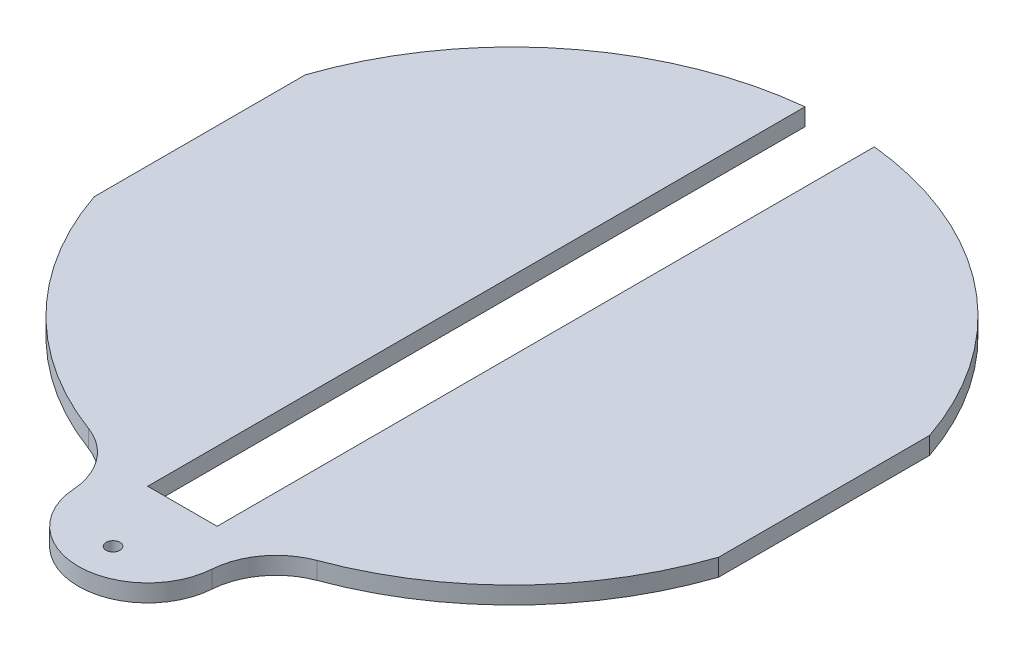
SolidWorks part; units mm, degrees
ref_plane "Front Plane" through (0, 0, 0) normal (0, 0, 1) x (1, 0, 0)
ref_plane "Top Plane" through (0, 0, 0) normal (0, 1, 0) x (1, 0, 0)
ref_plane "Right Plane" through (0, 0, 0) normal (1, 0, 0) x (0, 0, -1)
sketch "Sketch2" plane through (0, 0, 0) normal (0, 1, 0) x (1, 0, 0)
  line L0 (6.35, 63.5) -> (57.15, 63.5)
  line L1 (-57.15, -63.5) -> (-12.7, -63.5)
  line L2 (-57.15, -63.5) -> (-57.15, 63.5)
  line L3 (-57.15, 63.5) -> (-6.35, 63.5)
  line L4 (57.15, -63.5) -> (57.15, 63.5)
  line L5 (-57.15, -63.5) -> (57.15, 63.5) construction
  line L6 (-57.15, 63.5) -> (57.15, -63.5) construction
  line L7 (-6.35, -57.15) -> (6.35, -57.15)
  line L8 (-6.35, -57.15) -> (-6.35, 63.5)
  line L10 (6.35, -57.15) -> (6.35, 63.5)
  line L11 (-6.35, -57.15) -> (6.35, 63.5) construction
  line L12 (-6.35, 63.5) -> (6.35, -57.15) construction
  line L13 (12.7, -63.5) -> (57.15, -63.5)
  arc A0 (-12.7, -63.5) -> (12.7, -63.5) centre (0, -63.5) ccw
  point P0 (0, 0)
  point P6 (0, 3.175)
  point P12 (0, 0)
  point P15 (0, 0)
  dimension "D5" = 12.7
  dimension "D1" = 127
  dimension "D2" = 114.3
  dimension "D3" = 12.7
  dimension "D4" = 120.65
extrude "Boss-Extrude1" add sketch "Sketch2" along normal blind 3.175 contours L3 L8 L7 L10 L0 L4 L13 A0 L1 L2
sketch "Sketch3" plane through (0, 3.175, 0) normal (0, 1, 0) x (1, 0, 0)
  line L1 (-6.35, -57.15) -> (6.35, -57.15) construction
  circle A0 centre (0, -69.85) radius 1.27
  dimension "D1" = 2.54
  dimension "D2" = 12.7
extrude "Cut-Extrude1" cut sketch "Sketch3" against normal through all
sketch "Sketch4" plane through (0, 3.175, 0) normal (0, 1, 0) x (1, 0, 0)
  line L0 (-6.35, 3.175) -> (83.1266, 3.175) construction
  line L2 (-6.35, -57.15) -> (-6.35, 63.5) construction
  line L7 (0, 0) -> (0, 96.6328) construction
  line L8 (6.35, 63.5) -> (57.15, 63.5) construction
  line L9 (-12.7, -63.5) -> (-12.7, -55.798)
  line L10 (-57.15, 63.5) -> (57.15, 63.5)
  line L11 (-57.15, 63.5) -> (-57.15, 22.4878)
  line L12 (-57.15, -63.5) -> (-12.7, -63.5)
  line L13 (57.15, 63.5) -> (57.15, 22.4878)
  line L14 (12.7, -63.5) -> (12.7, -55.798)
  line L15 (57.15, -16.1378) -> (57.15, -63.5)
  line L16 (-57.15, -16.1378) -> (-57.15, -63.5)
  line L17 (12.7, -63.5) -> (57.15, -63.5)
  arc A1 (-57.15, -16.1378) -> (-12.7, -55.798) centre (0, 3.175) ccw
  arc A2 (57.15, 22.4878) -> (-57.15, 22.4878) centre (0, 3.175) ccw
  arc A3 (12.7, -55.798) -> (57.15, -16.1378) centre (0, 3.175) ccw
  line M11 (-57.15, 63.5) -> (-57.15, -63.5)
  line M12 (-57.15, -63.5) -> (-12.7, -63.5)
  line M14 (12.7, -63.5) -> (57.15, -63.5)
  line M15 (57.15, -63.5) -> (57.15, 63.5)
  line M16 (57.15, 63.5) -> (6.35, 63.5)
  line M17 (6.35, 63.5) -> (6.35, -57.15)
  line M19 (-6.35, -57.15) -> (-6.35, 63.5)
  line M20 (-6.35, 63.5) -> (-57.15, 63.5)
extrude "Cut-Extrude2" cut sketch "Sketch4" against normal through all both and the other way through all contours A1 L9 M11 M12 | A2 M19 M20 M11 | A3 L14 M14 M15 | A2 M15 M16 M17
fillet "Fillet1" radius 12.7 2 edges at (12.7, 1.5875, 55.798) (-12.7, 1.5875, 55.798)
